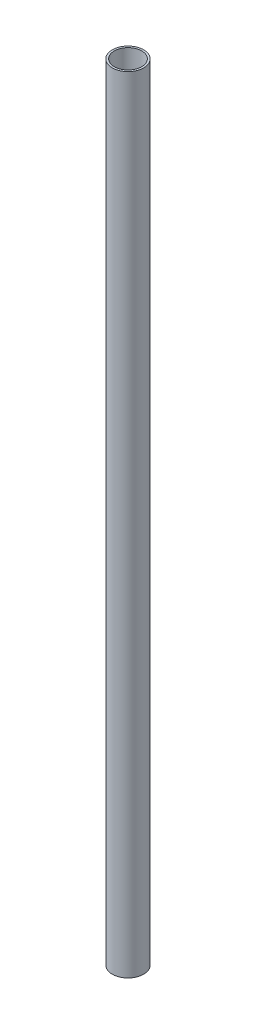
SolidWorks part; units mm, degrees
material "Thornel Mat VMA"
ref_plane "Front Plane" through (0, 0, 0) normal (0, 0, 1) x (1, 0, 0)
ref_plane "Top Plane" through (0, 0, 0) normal (0, 1, 0) x (1, 0, 0)
ref_plane "Right Plane" through (0, 0, 0) normal (1, 0, 0) x (0, 0, -1)
sketch "Sketch1" plane through (0, 0, 0) normal (0, 1, 0) x (1, 0, 0)
  circle A0 centre (0, 0) radius 8
  circle A1 centre (0, 0) radius 7
  dimension "D1" = 16
  dimension "D2" = 14
extrude "Boss-Extrude1" add sketch "Sketch1" along normal mid plane 400
